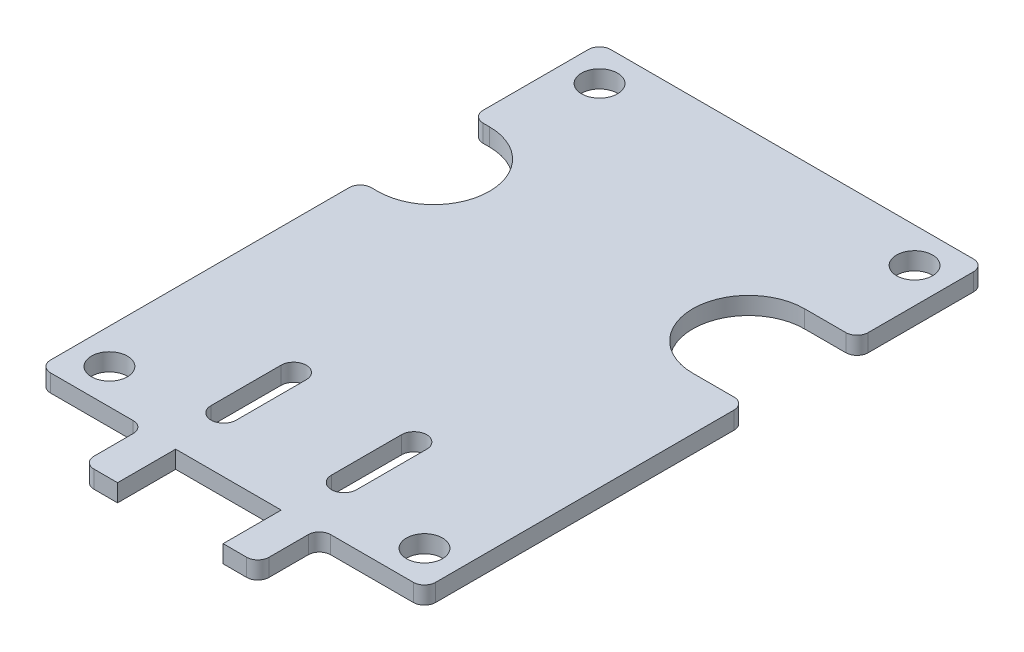
SolidWorks part; units mm, degrees
ref_plane "Front Plane" through (0, 0, 0) normal (0, 0, 1) x (1, 0, 0)
ref_plane "Top Plane" through (0, 0, 0) normal (0, 1, 0) x (1, 0, 0)
ref_plane "Right Plane" through (0, 0, 0) normal (1, 0, 0) x (0, 0, -1)
sketch "Sketch1" plane through (0, 0, 0) normal (0, 1, 0) x (1, 0, 0)
  line L0 (17.4625, -25.4) -> (17.4625, 25.4)
  line L1 (-14.2875, -22.225) -> (14.2875, -22.225) construction
  line L2 (-14.2875, -22.225) -> (-14.2875, 22.225) construction
  line L3 (-14.2875, 22.225) -> (14.2875, 22.225) construction
  line L4 (14.2875, -22.225) -> (14.2875, 22.225) construction
  line L5 (-14.2875, -22.225) -> (14.2875, 22.225) construction
  line L6 (-14.2875, 22.225) -> (14.2875, -22.225) construction
  line L7 (-17.4625, 25.4) -> (17.4625, 25.4)
  line L8 (-17.4625, -25.4) -> (-17.4625, 25.4)
  line L9 (-17.4625, -25.4) -> (17.4625, -25.4)
  point P0 (0, 0)
  dimension "D1" = 44.45
  dimension "D2" = 28.575
  dimension "D3" = 3.175
extrude "Boss-Extrude1" add sketch "Sketch1" along normal blind 1.5875
hole_wizard "#4 Clearance Hole1" positions "Sketch4" profile "Sketch5" hole size "#4" standard "ANSI Inch" end condition through all
sketch "Sketch4" plane through (0, 1.5875, 0) normal (0, 1, 0) x (1, 0, 0)
  point P0 (-14.2875, 22.225)
  point P3 (14.2875, 22.225)
  point P6 (14.2875, -22.225)
  point P9 (-14.2875, -22.225)
sketch "Sketch5" plane through (-14.2875, 1.5875, -22.225) normal (1, 0, 0) x (0, 0, 1)
  line L0 (0, 0) -> (0, 1.5875)
  line L1 (0, 1.5875) -> (1.6319, 1.5875)
  line L2 (1.6319, 1.5875) -> (1.6319, 0)
  line L5 (1.6319, 0) -> (0, 0)
  line L11 (0, -6.35) -> (0, 107.95) construction
  dimension "Thru Hole Dia." = 3.2639
  dimension "Thru Hole Depth" = 1.5875
sketch "Sketch6" plane through (0, 1.5875, 0) normal (0, 1, 0) x (1, 0, 0)
  line L0 (7.9375, -25.4) -> (7.9375, -30.988)
  line L1 (7.9375, -30.988) -> (-7.9375, -30.988)
  line L2 (-7.9375, -30.988) -> (-7.9375, -25.4)
  line L3 (-7.9375, -25.4) -> (7.9375, -25.4)
  line L4 (0, -30.988) -> (0, -25.4) construction
  line L5 (-17.4625, -25.4) -> (17.4625, -25.4) construction
  circle A0 centre (14.2875, -22.225) radius 1.632 construction
  dimension "D1" = 8.763
  dimension "D2" = 15.875
extrude "Boss-Extrude2" add sketch "Sketch6" against normal up to surface (1.5875 mm away) up to face at (-14.2875, 0, -20.593)
sketch "Sketch7" plane through (0, 1.5875, 0) normal (0, 1, 0) x (1, 0, 0)
  line L0 (-15.875, 13.8303) -> (-20.9423, 13.8303)
  line L5 (-20.9423, 13.8303) -> (-20.9423, 8.763)
  line L6 (-20.9423, 8.763) -> (-20.9423, 3.6957)
  line L11 (-20.9423, 3.6957) -> (-15.875, 3.6957)
  line L12 (12.7, 13.8303) -> (17.7673, 13.8303)
  line L13 (17.7673, 13.8303) -> (17.7673, 8.763)
  line L14 (17.7673, 3.6957) -> (12.7, 3.6957)
  line L15 (17.7673, 3.6957) -> (17.7673, 8.763)
  circle A0 centre (-15.875, 8.763) radius 4.8133 construction
  circle A1 centre (12.7, 8.763) radius 4.8133 construction
  circle A2 centre (-15.875, 8.763) radius 4.8133 construction
  circle A3 centre (12.7, 8.763) radius 4.8133 construction
  arc A4 (-15.875, 3.6957) -> (-15.875, 13.8303) centre (-15.875, 8.763) ccw
  arc A5 (12.7, 13.8303) -> (12.7, 3.6957) centre (12.7, 8.763) ccw
  circle A6 centre (12.7, 8.763) radius 5.0673 construction
  circle A7 centre (-15.875, 8.763) radius 5.0673 construction
  dimension "D1" = 0.254
extrude "Cut-Extrude1" cut sketch "Sketch7" against normal through all
sketch "Sketch8" plane through (0, 1.5875, 0) normal (0, 1, 0) x (1, 0, 0)
  line L0 (5.461, -14.3429) -> (5.461, -20.6929) construction
  line L1 (6.604, -14.3429) -> (6.604, -20.6929)
  line L2 (4.318, -14.3429) -> (4.318, -20.6929)
  line L3 (-0.8731, 0) -> (0.8731, 0) construction
  line L5 (0, -0.8731) -> (0, 0.8731) construction
  arc A0 (6.604, -14.3429) -> (4.318, -14.3429) centre (5.461, -14.3429) ccw
  arc A1 (4.318, -20.6929) -> (6.604, -20.6929) centre (5.461, -20.6929) ccw
  point P2 (5.461, -17.5179)
  point P11 (5.2326, -17.5179)
  point P12 (0, 0)
  dimension "D1" = 2.286
  dimension "D2" = 6.35
  dimension "D3" = 5.461
  dimension "D4" = 17.5179
extrude "Cut-Extrude2" cut sketch "Sketch8" against normal through all
mirror "Mirror1" about plane through (0, 0, 0) normal (1, 0, 0) of "Cut-Extrude2"
sketch "Sketch9" plane through (0, 0, 0) normal (0, -1, 0) x (1, 0, 0)
  line L0 (7.9375, 30.988) -> (-7.9375, 30.988) construction
  line L1 (-4.7868, 36.2581) -> (4.7868, 36.2581)
  line L2 (-4.7868, 36.2581) -> (-4.7868, 25.7179)
  line L3 (-4.7868, 25.7179) -> (4.7868, 25.7179)
  line L4 (4.7868, 36.2581) -> (4.7868, 25.7179)
  line L5 (-4.7868, 36.2581) -> (4.7868, 25.7179) construction
  line L6 (-4.7868, 25.7179) -> (4.7868, 36.2581) construction
  point P0 (0, 30.988)
  dimension "D1" = 9.5736
  dimension "D2" = 5.2701
extrude "Cut-Extrude3" cut sketch "Sketch9" against normal through all
fillet "Fillet1" radius 1.016 12 edges at (-17.4625, 0.7937, 25.4) (-7.9375, 0.7937, 25.4) (-7.9375, 0.7937, 30.988) (7.9375, 0.7937, 25.4) (17.4625, 0.7937, 25.4) (17.4625, 0.7937, -3.6957) (17.4625, 0.7937, -13.8303) (17.4625, 0.7937, -25.4) (-17.4625, 0.7937, -25.4) (-17.4625, 0.7937, -13.8303) (-17.4625, 0.7937, -3.6957) (7.9375, 0.7937, 30.988)
